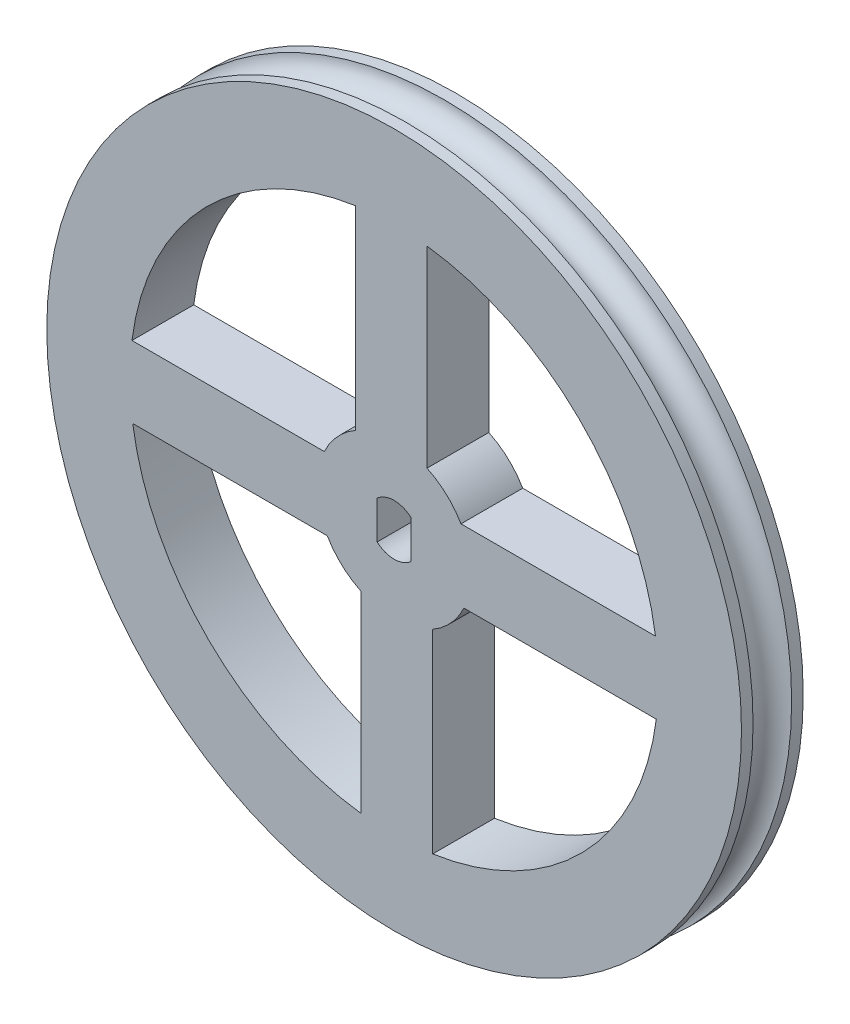
SolidWorks part; units mm, degrees
ref_plane "Front Plane" through (0, 0, 0) normal (0, 0, 1) x (1, 0, 0)
ref_plane "Top Plane" through (0, 0, 0) normal (0, 1, 0) x (1, 0, 0)
ref_plane "Right Plane" through (0, 0, 0) normal (1, 0, 0) x (0, 0, -1)
sketch "Sketch1" plane through (0, 0, 0) normal (0, 1, 0) x (1, 0, 0)
  line L0 (-57.15, 0) -> (-57.15, -1.905)
  line L1 (0, 0) -> (-57.15, 0)
  line L2 (0, 0) -> (0, -10.16)
  line L3 (0, -10.16) -> (-57.15, -10.16)
  line L4 (-57.15, 0) -> (-57.15, -10.16) construction
  line L5 (-57.15, -8.255) -> (-57.15, -10.16)
  circle A0 centre (-57.15, -5.08) radius 3.175 construction
  arc A1 (-57.15, -1.905) -> (-57.15, -8.255) centre (-57.15, -5.08) cw
  dimension "D1" = 57.15
  dimension "D2" = 10.16
revolve "Revolve1" add sketch "Sketch1" angle 360 about L2
sketch "Sketch3" plane through (0, 0, 0) normal (0, 0, -1) x (-1, 0, 0)
  line L18 (-6.35, 43.0041) -> (-6.35, 10.9985) construction
  line L19 (-6.35, 10.9985) -> (6.35, 10.9985) construction
  line L20 (6.35, 10.9985) -> (6.35, 43.0041) construction
  line L21 (6.35, 43.0041) -> (-6.35, 43.0041) construction
  line L22 (43.0041, -7.2894) -> (43.0041, 5.4106) construction
  line L23 (43.0041, 5.4106) -> (10.9985, 5.4106) construction
  line L24 (5.4106, -10.9985) -> (-7.2894, -10.9985) construction
  line L25 (10.9985, -7.2894) -> (43.0041, -7.2894) construction
  line L26 (10.9985, 5.4106) -> (10.9985, -7.2894) construction
  line L27 (-7.2894, -43.9435) -> (5.4106, -43.9435) construction
  line L28 (5.4106, -43.9435) -> (5.4106, -11.9379) construction
  line L29 (-7.2894, -11.9379) -> (-7.2894, -43.9435) construction
  line L30 (5.4106, -11.9379) -> (-7.2894, -11.9379) construction
  line L31 (-43.9435, 6.35) -> (-43.9435, -6.35) construction
  line L32 (-43.9435, -6.35) -> (-11.9379, -6.35) construction
  line L33 (-11.9379, 6.35) -> (-43.9435, 6.35) construction
  line L34 (-11.9379, -6.35) -> (-11.9379, 6.35) construction
  line L35 (6.35, 43.0041) -> (6.35, 10.9985)
  line L36 (11.4898, 5.4106) -> (43.1324, 5.4106)
  line L37 (5.4106, -11.4898) -> (5.4106, -43.1324)
  line L38 (43.0041, -6.35) -> (10.9985, -6.35)
  line L39 (-10.9985, -5.4106) -> (-10.9985, 7.2894) construction
  line L40 (-11.4898, -5.4106) -> (-43.1324, -5.4106)
  line L41 (-6.35, -43.0041) -> (-6.35, -10.9985)
  line L42 (-5.4106, 10.9985) -> (7.2894, 10.9985) construction
  line L43 (-5.4106, 11.4898) -> (-5.4106, 43.1324)
  line L44 (-43.0041, 6.35) -> (-10.9985, 6.35)
  circle A4 centre (0, 0) radius 12.7 construction
  circle A5 centre (0, 0) radius 43.4704 construction
  arc A6 (6.35, 43.0041) -> (43.1324, 5.4106) centre (0, 0) cw
  arc A7 (6.35, 10.9985) -> (11.4898, 5.4106) centre (0, 0) cw
  arc A8 (43.0041, -6.35) -> (5.4106, -43.1324) centre (0, 0) cw
  arc A9 (10.9985, -6.35) -> (5.4106, -11.4898) centre (0, 0) cw
  arc A10 (-6.35, -43.0041) -> (-43.1324, -5.4106) centre (0, 0) cw
  arc A11 (-6.35, -10.9985) -> (-11.4898, -5.4106) centre (0, 0) cw
  arc A12 (-43.0041, 6.35) -> (-5.4106, 43.1324) centre (0, 0) cw
  arc A13 (-10.9985, 6.35) -> (-5.4106, 11.4898) centre (0, 0) cw
  point P23 (-0.4697, -0.4697)
  point P43 (0, 0)
  dimension "D1" = 12.7
  dimension "D2" = 4
  dimension "D3" = 25.4
extrude "Cut-Extrude2" cut sketch "Sketch3" against normal through all
sketch "Sketch6" plane through (0, 0, 0) normal (0, 0, -1) x (-1, 0, 0)
  line L0 (-2.794, 3.1238) -> (-2.794, -3.1238)
  line L1 (2.794, 3.1238) -> (2.794, -3.1238)
  circle A0 centre (0, 0) radius 4.191 construction
  arc A1 (-2.794, -3.1238) -> (2.794, -3.1238) centre (0, 0) ccw
  arc A2 (2.794, 3.1238) -> (-2.794, 3.1238) centre (0, 0) ccw
  dimension "D1" = 5.588
  dimension "D3" = 8.382
  dimension "D2" = 2.794
extrude "Cut-Extrude3" cut sketch "Sketch6" against normal through all
